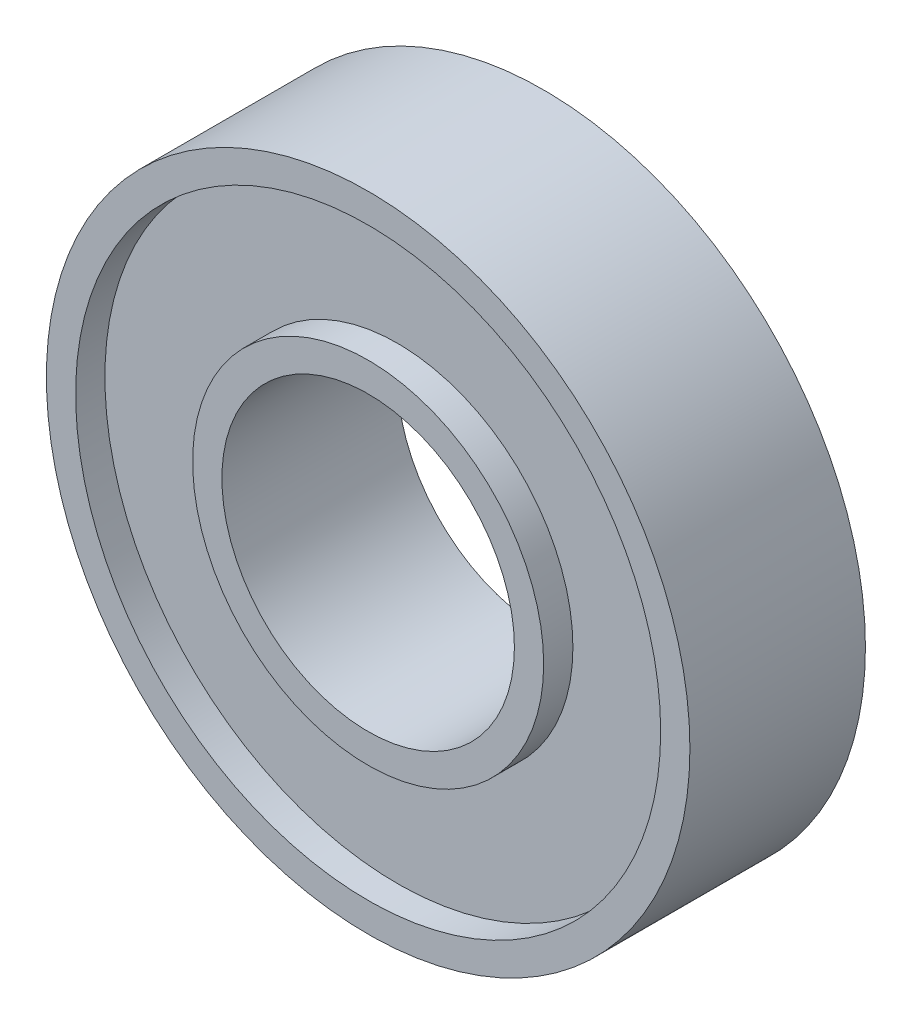
SolidWorks part; units mm, degrees
material "ｽﾃﾝﾚｽ鋼(ｸﾛﾑ)"
ref_plane "正面" through (0, 0, 0) normal (0, 0, 1) x (1, 0, 0)
ref_plane "平面" through (0, 0, 0) normal (0, 1, 0) x (1, 0, 0)
ref_plane "右側面" through (0, 0, 0) normal (1, 0, 0) x (0, 0, -1)
sketch "ｽｹｯﾁ1" plane through (0, 0, 0) normal (1, 0, 0) x (0, 0, -1)
  line L0 (0, 0) -> (0, -50000) construction
  line L1 (0, 0) -> (50000, 0) construction
  line L2 (3, 11) -> (-3, 11)
  line L3 (-3, 11) -> (-3, 10)
  line L4 (-3, 10) -> (-2, 10)
  line L5 (-2, 10) -> (-2, 6)
  line L6 (-2, 6) -> (-3, 6)
  line L7 (-3, 6) -> (-3, 5)
  line L8 (-3, 5) -> (3, 5)
  line L9 (3, 6) -> (3, 5)
  line L10 (2, 6) -> (3, 6)
  line L11 (2, 10) -> (2, 6)
  line L12 (3, 10) -> (2, 10)
  line L13 (3, 11) -> (3, 10)
  point P14 (0, 5)
  point P19 (0, 11)
  dimension "D1" = 6
  dimension "D2" = 10
  dimension "D3" = 22
  dimension "D4" = 12
  dimension "D5" = 20
  dimension "D6" = 1
revolve "回転1" add sketch "ｽｹｯﾁ1" angle 360 about L1
